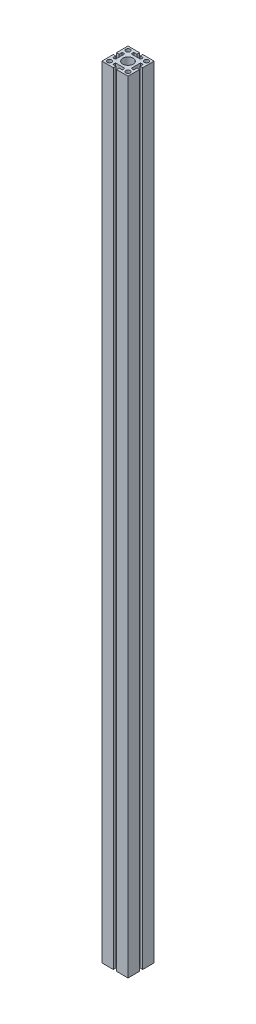
SolidWorks part; units mm, degrees
ref_plane "Front Plane" through (0, 0, 0) normal (0, 0, 1) x (1, 0, 0)
ref_plane "Top Plane" through (0, 0, 0) normal (0, 1, 0) x (1, 0, 0)
ref_plane "Right Plane" through (0, 0, 0) normal (1, 0, 0) x (0, 0, -1)
sketch "Sketch1" plane through (0, 0, 0) normal (0, 1, 0) x (1, 0, 0)
  line L1 (-25, -3) -> (-25, -25)
  line L6 (9, 20) -> (9, 15)
  line L7 (9, 20) -> (3, 20)
  line L8 (9, 15) -> (-9, 15)
  line L9 (3, 20) -> (3, 25)
  line L10 (-3, 25) -> (-25, 25)
  line L11 (-25, 25) -> (-25, 3)
  line L12 (-25, -25) -> (-3, -25)
  line L13 (25, -25) -> (25, -3)
  line L14 (3, 25) -> (25, 25)
  line L15 (-3, 20) -> (-3, 25)
  line L16 (-9, 20) -> (-9, 15)
  line L17 (3, -25) -> (25, -25)
  line L18 (25, 3) -> (25, 25)
  line L19 (-3, 20) -> (-9, 20)
  line L21 (-20, 9) -> (-15, 9)
  line L22 (-20, 9) -> (-20, 3)
  line L24 (-15, 9) -> (-15, -9)
  line L27 (-20, 3) -> (-25, 3)
  line L28 (20, -9) -> (15, -9)
  line L29 (20, -9) -> (20, -3)
  line L30 (15, -9) -> (15, 9)
  line L31 (20, -3) -> (25, -3)
  line L32 (20, 3) -> (25, 3)
  line L33 (-20, -3) -> (-25, -3)
  line L34 (20, 9) -> (15, 9)
  line L35 (20, 3) -> (20, 9)
  line L40 (-20, -9) -> (-15, -9)
  line L41 (-20, -3) -> (-20, -9)
  line L42 (-9, -20) -> (-9, -15)
  line L43 (-9, -20) -> (-3, -20)
  line L44 (-9, -15) -> (9, -15)
  line L45 (-3, -20) -> (-3, -25)
  line L46 (3, -20) -> (3, -25)
  line L47 (9, -20) -> (9, -15)
  line L48 (3, -20) -> (9, -20)
  circle A0 centre (0, 0) radius 10
  circle A1 centre (-17.6777, 17.6777) radius 4.1387
  circle A2 centre (17.6777, 17.6777) radius 4.1387
  circle A3 centre (17.6777, -17.6777) radius 4.1387
  circle A4 centre (-17.6777, -17.6777) radius 4.1387
  point P44 (0, 0)
  point P46 (0, 0)
  dimension "D1" = 4
extrude "Boss-Extrude1" add sketch "Sketch1" along normal blind 1494
